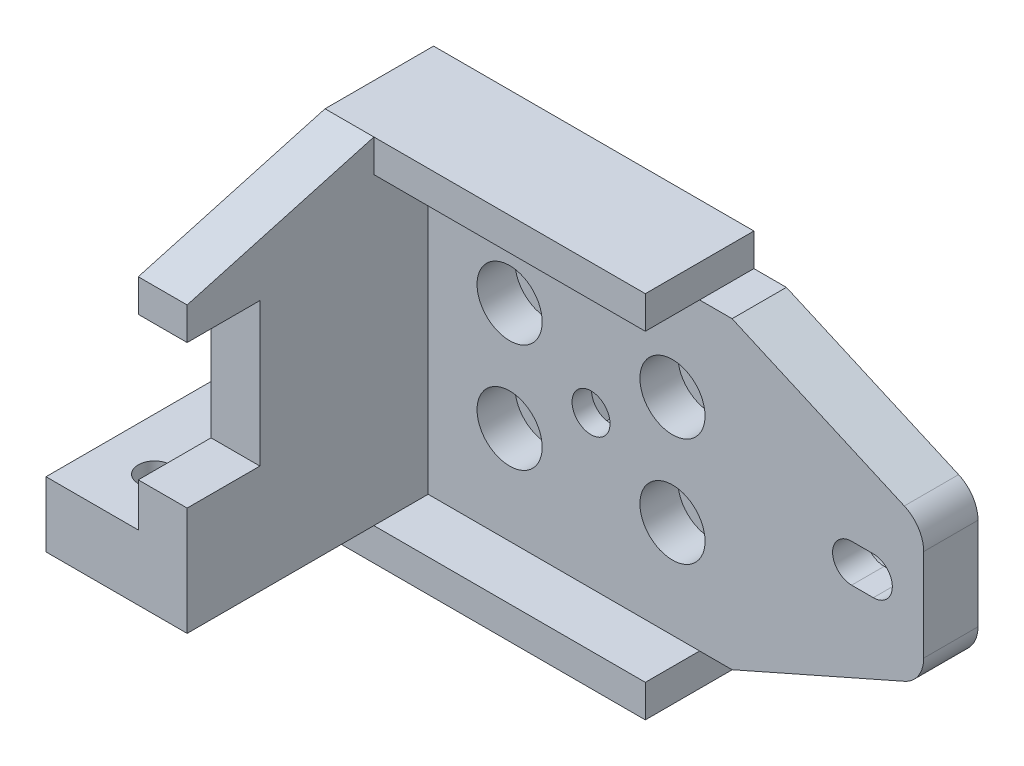
SolidWorks part; units mm, degrees
material "自定义塑料"
ref_plane "前视基准面" through (0, 0, 0) normal (0, 0, 1) x (1, 0, 0)
ref_plane "上视基准面" through (0, 0, 0) normal (0, 1, 0) x (1, 0, 0)
ref_plane "右视基准面" through (0, 0, 0) normal (1, 0, 0) x (0, 0, -1)
sketch "草图1" plane through (0, 0, 0) normal (0, 0, 1) x (1, 0, 0)
  line L1 (0, 0) -> (-20, 0)
  line L2 (0, 0) -> (0, 34)
  line L3 (0, 34) -> (-20, 34)
  line L4 (-20, 0) -> (-20, 34)
  dimension "D1" = 34
  dimension "D2" = 20
extrude "凸台-拉伸1" add sketch "草图1" along normal blind 5
sketch "草图2" plane through (0, 0, 5) normal (0, 0, 1) x (1, 0, 0)
  line L0 (0, 0) -> (0, 34) construction
  line L1 (-20, 34) -> (0, 34)
  line L2 (-20, 34) -> (-20, 31)
  line L3 (-20, 31) -> (0, 31)
  line L4 (0, 34) -> (0, 31)
  line L6 (-20, 0) -> (0, 0)
  line L7 (-20, 0) -> (-20, 3)
  line L8 (-20, 3) -> (0, 3)
  line L9 (0, 0) -> (0, 3)
  dimension "D1" = 3
  dimension "D2" = 3
extrude "凸台-拉伸2" add sketch "草图2" along normal blind 5
sketch "草图4" plane through (0, 0, 0) normal (0, 0, -1) x (-1, 0, 0)
  line L0 (-1047.5681, 17) -> (-20.6407, 17) construction
  line L1 (0, 0) -> (0, 34) construction
  line L2 (20, 34) -> (20, 0) construction
  line L3 (0, 31) -> (-2.9917, 31)
  line L4 (-2.9917, 31) -> (-20.6407, 23.2036)
  line L5 (-20.6407, 23.2036) -> (-20.6407, 10.7964)
  line L6 (0, 3) -> (-2.9917, 3)
  line L7 (-2.9917, 3) -> (-20.6407, 10.7964)
  line L8 (0, 31) -> (0, 3)
  line L9 (0, 31) -> (0, 3)
  line L10 (-16, 18.75) -> (-14, 18.75)
  line L11 (-16, 15.25) -> (-14, 15.25)
  line L14 (0, 17) -> (50000, 17) construction
  arc A0 (-16, 18.75) -> (-16, 15.25) centre (-16, 17) ccw
  arc A1 (-14, 15.25) -> (-14, 18.75) centre (-14, 17) ccw
  point P4 (0, 17)
  point P7 (20, 17)
  point P19 (-20.6407, 17)
  line M1 (0, 34) -> (0, 0)
  dimension "D1" = 3.5
  dimension "D2" = 3.5
  dimension "D3" = 2
  dimension "D4" = 14
  dimension "D5" = 28
extrude "凸台-拉伸3" add sketch "草图4" against normal blind 5 contours L7 L6 L3 L4 L5 A1 L11 A0 L10 M1
fillet "圆角1" radius 3 2 edges at (20.6407, 23.2036, 2.5) (20.6407, 10.7964, 2.5)
sketch "草图5" plane through (0, 0, 0) normal (0, 0, -1) x (-1, 0, 0)
  line L0 (-16, 20.25) -> (-13.5058, 20.2122)
  line L1 (-16, 13.75) -> (-14, 13.75)
  arc A0 (-16, 20.25) -> (-16, 13.75) centre (-16, 17) ccw
  arc A1 (-14, 13.75) -> (-13.5058, 20.2122) centre (-14, 17) ccw
  dimension "D1" = 6.5
  dimension "D2" = 6.5
extrude "切除-拉伸1" cut sketch "草图5" against normal blind 2
sketch "草图7" plane through (0, 0, 5) normal (0, 0, 1) x (1, 0, 0)
  line L0 (-20, 17) -> (20.6407, 17) construction
  line L1 (-20, 31) -> (-20, 3) construction
  line L2 (20.6407, 21.2491) -> (20.6407, 12.7509) construction
  line L3 (-10, 34) -> (-10, 0) construction
  line L4 (0, 34) -> (-20, 34) construction
  line L5 (-20, 0) -> (0, 0) construction
  circle A0 centre (-17.5, 22) radius 1.6
  circle A1 centre (-2.5, 22) radius 1.6
  circle A2 centre (-2.5, 12) radius 1.6
  circle A3 centre (-17.5, 12) radius 1.6
  dimension "D1" = 3.2
  dimension "D2" = 10
  dimension "D3" = 15
extrude "切除-拉伸2" cut sketch "草图7" against normal through all
sketch "草图8" plane through (0, 0, 5) normal (0, 0, 1) x (1, 0, 0)
  line L0 (-10, 3) -> (-10, 31) construction
  line L1 (0, 3) -> (-20, 3) construction
  line L2 (-20, 31) -> (0, 31) construction
  line L3 (-20, 17) -> (-10, 17) construction
  line L4 (-20, 31) -> (-20, 3) construction
  circle A0 centre (-10, 17) radius 1.75
  dimension "D1" = 3.5
extrude "切除-拉伸3" cut sketch "草图8" against normal through all
sketch "草图9" plane through (0, 0, 0) normal (0, 0, -1) x (-1, 0, 0)
  line L1 (11.6688, 13.9643) -> (13.4633, 16.9274)
  line L2 (13.4633, 16.9274) -> (11.7946, 19.963)
  line L3 (11.7946, 19.963) -> (8.3312, 20.0357)
  line L4 (8.3312, 20.0357) -> (6.5367, 17.0726)
  line L5 (6.5367, 17.0726) -> (8.2054, 14.037)
  line L6 (8.2054, 14.037) -> (11.6688, 13.9643)
  circle A0 centre (10, 17) radius 3 construction
  dimension "D1" = 6
extrude "切除-拉伸5" cut sketch "草图9" against normal blind 3.2
sketch "草图12" plane through (-20, 0, 0) normal (-1, 0, 0) x (0, 0, 1)
  line L0 (5, 3) -> (10, 3)
  line L2 (5, 3) -> (5, 34)
  line L3 (5, 34) -> (0, 34)
  line L4 (0, 3) -> (0, 34)
  line L5 (10, 3) -> (10, 0)
  line L6 (10, 0) -> (0, 0)
  line L7 (0, 0) -> (0, 3)
  line L8 (0, 3) -> (0.0538, 3.0805)
extrude "凸台-拉伸17" add sketch "草图12" along normal blind 18
sketch "草图14" plane through (0, 0, 5) normal (0, 0, 1) x (1, 0, 0)
  line L0 (-38, 34) -> (-20, 34) construction
  line L1 (-25, 34) -> (-38, 34)
  line L2 (-25, 34) -> (-25, 3)
  line L3 (-25, 3) -> (-38, 3)
  line L4 (-38, 34) -> (-38, 3)
  line L5 (-20, 34) -> (-20, 31) construction
  dimension "D1" = 5
extrude "凸台-拉伸18" add sketch "草图14" along normal blind 30
sketch "草图15" plane through (0, 3, 0) normal (0, -1, 0) x (1, 0, 0)
  line L0 (0, 5) -> (-25, 5) construction
  line L1 (-25, 35) -> (-25, 10) construction
  line L3 (-43.0012, 27.2) -> (-22.5305, 27.2)
  line L4 (-43.0012, 27.2) -> (-43.0012, 38.0035)
  line L5 (-43.0012, 38.0035) -> (-22.5305, 38.0035)
  line L6 (-22.5305, 27.2) -> (-22.5305, 38.0035)
  circle A0 centre (-33.2, 22) radius 1.5
  point P4 (-25, 22.5)
  dimension "D1" = 3
  dimension "D2" = 17
  dimension "D3" = 8.2
  dimension "D4" = 5.2
extrude "切除-拉伸6" cut sketch "草图15" against normal through all
sketch "草图16" plane through (0, 34, 0) normal (0, 1, 0) x (1, 0, 0)
  line L1 (-25, -27.2) -> (-41.4444, -27.2)
  line L2 (-25, -27.2) -> (-25, 1.0812)
  line L3 (-25, 1.0812) -> (-41.4444, 1.0812)
  line L4 (-41.4444, -27.2) -> (-41.4444, 1.0812)
extrude "切除-拉伸7" cut sketch "草图16" against normal blind 25
sketch "草图17" plane through (-20, 0, 0) normal (-1, 0, 0) x (0, 0, 1)
  line L0 (10, 34) -> (10, 31) construction
  line L1 (10, 34) -> (5, 34)
  line L2 (10, 34) -> (10, 31)
  line L3 (10, 31) -> (5, 31)
  line L4 (5, 34) -> (5, 31)
  line L5 (10, 34) -> (5, 34) construction
extrude "凸台-拉伸19" add sketch "草图17" along normal up to surface (5 mm away) up to face at (-25, 21.5, 2.5)
sketch "草图18" plane through (0, 0, 5) normal (0, 0, 1) x (1, 0, 0)
  circle A0 centre (-17.5, 22) radius 3
  circle A1 centre (-2.5, 22) radius 3
  circle A2 centre (-2.5, 12) radius 3
  circle A3 centre (-17.5, 12) radius 3
  dimension "D1" = 6
  dimension "D2" = 6
  dimension "D3" = 6
  dimension "D4" = 6
extrude "切除-拉伸8" cut sketch "草图18" against normal blind 3.5
sketch "草图19" plane through (0, 9, 0) normal (0, 1, 0) x (1, 0, 0)
  line L0 (-38, -27.2) -> (-25, -27.2) construction
  line L1 (-25, 0) -> (-29.5, 0)
  line L2 (-25, 0) -> (-25, -27.2)
  line L3 (-25, -27.2) -> (-29.5, -27.2)
  line L4 (-29.5, 0) -> (-29.5, -27.2)
  dimension "D1" = 4.5
extrude "凸台-拉伸20" add sketch "草图19" along normal up to surface (25 mm away) up to face at (-12.5, 34, 5)
sketch "草图20" plane through (-25, 0, 0) normal (1, 0, 0) x (0, 0, -1)
  line L0 (-5, 3) -> (-5, 31) construction
  line L1 (-28.5, 26.2) -> (-20.5, 26.2)
  line L2 (-28.5, 26.2) -> (-28.5, 13)
  line L3 (-28.5, 13) -> (-20.5, 13)
  line L4 (-20.5, 26.2) -> (-20.5, 13)
  line L5 (-27.2, 3) -> (-10, 3) construction
  line L6 (-10, 34) -> (-27.2, 29.2)
  line L7 (-27.2, 34) -> (-27.2, 3) construction
  line L8 (-27.2, 29.2) -> (-27.2, 34)
  line L9 (-27.2, 34) -> (-10, 34)
  dimension "D1" = 13.2
  dimension "D2" = 8
  dimension "D3" = 15.5
  dimension "D4" = 10
  dimension "D5" = 3
extrude "切除-拉伸9" cut sketch "草图20" against normal through all
